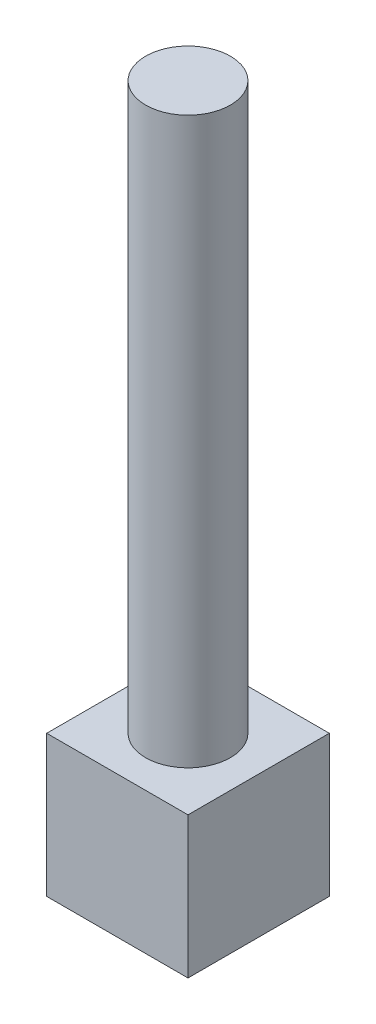
SolidWorks part; units mm, degrees
ref_plane "前视基准面" through (0, 0, 0) normal (0, 0, 1) x (1, 0, 0)
ref_plane "上视基准面" through (0, 0, 0) normal (0, 1, 0) x (1, 0, 0)
ref_plane "右视基准面" through (0, 0, 0) normal (1, 0, 0) x (0, 0, -1)
sketch "草图2" plane through (0, 0, 0) normal (0, 1, 0) x (1, 0, 0)
  line L1 (-33.988, 8.7353) -> (-23.988, 8.7353)
  line L2 (-33.988, 8.7353) -> (-33.988, -1.2647)
  line L3 (-33.988, -1.2647) -> (-23.988, -1.2647)
  line L4 (-23.988, 8.7353) -> (-23.988, -1.2647)
  line L5 (-28.988, -1.2647) -> (-28.988, 8.7353) construction
  line L6 (-33.988, 3.7353) -> (-23.988, 3.7353) construction
  dimension "D1" = 10
  dimension "D2" = 10
extrude "凸台-拉伸2" add sketch "草图2" along normal blind 10
sketch "草图3" plane through (0, 10, 0) normal (0, 1, 0) x (1, 0, 0)
  line L0 (-23.988, 8.7353) -> (-33.988, 8.7353) construction
  line L1 (-23.988, -1.2647) -> (-23.988, 8.7353) construction
  circle A0 centre (-28.988, 3.7353) radius 3
  dimension "D1" = 5
  dimension "D2" = 5
extrude "凸台-拉伸3" add sketch "草图3" along normal blind 40
